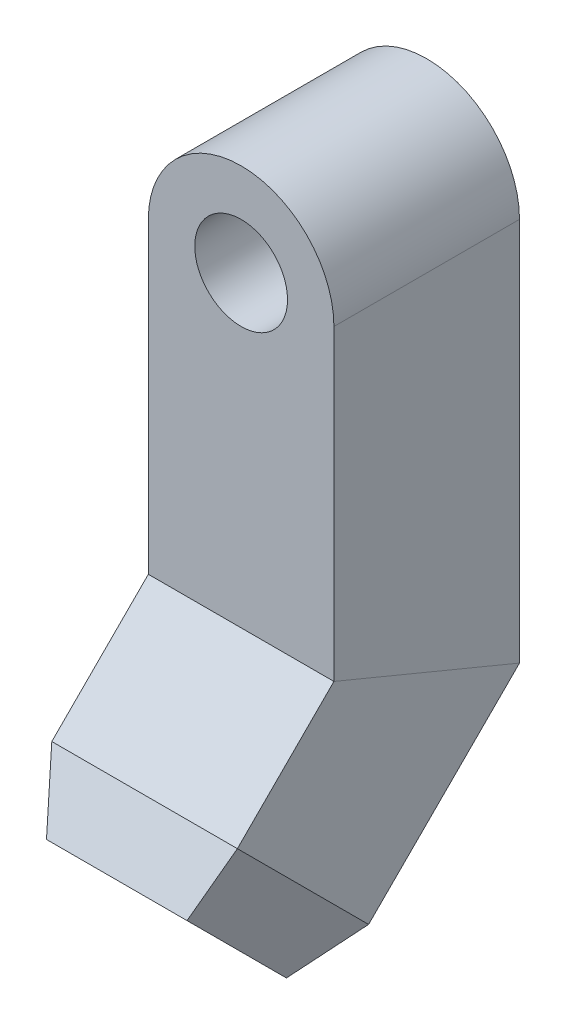
SolidWorks part; units mm, degrees
ref_plane "Front Plane" through (0, 0, 0) normal (0, 0, 1) x (1, 0, 0)
ref_plane "Top Plane" through (0, 0, 0) normal (0, 1, 0) x (1, 0, 0)
ref_plane "Right Plane" through (0, 0, 0) normal (1, 0, 0) x (0, 0, -1)
ref_plane "Plane2" through (0, 96.393, 0) normal (0, 1, 0) x (1, 0, 0)
sketch "Sketch10" plane through (0, 0, 0) normal (1, 0, 0) x (0, 0, -1)
  line L0 (0, 96.393) -> (0, 25.4)
  line L1 (55, 96.393) -> (-55, 96.393) construction
  line L2 (0, 25.4) -> (-25.4, 0)
  line L3 (55, 0) -> (-55, 0) construction
  dimension "D1" = 70.993
  dimension "D2" = 135
sketch "Sketch11" plane through (0, 96.393, 0) normal (0, 1, 0) x (1, 0, 0)
  line L1 (-19.05, -19.05) -> (19.05, -19.05)
  line L2 (-19.05, -19.05) -> (-19.05, 19.05)
  line L3 (-19.05, 19.05) -> (19.05, 19.05)
  line L4 (19.05, -19.05) -> (19.05, 19.05)
  line L5 (-19.05, -19.05) -> (19.05, 19.05) construction
  line L6 (-19.05, 19.05) -> (19.05, -19.05) construction
  point P0 (0, 0)
  dimension "D1" = 38.1
sweep "Sweep1" add profiles "Sketch11" path "Sketch10"
sketch "Sketch12" plane through (0, -12.7, 12.7) normal (0, -0.7071, 0.7071) x (1, 0, 0)
  line L8 (19.05, -1.0895) -> (19.05, 37.0105)
  line L9 (19.05, 37.0105) -> (-19.05, 37.0105)
  line L10 (-19.05, 37.0105) -> (-19.05, -1.0895)
  line L11 (-19.05, -1.0895) -> (19.05, -1.0895)
  line L12 (19.05, -1.0895) -> (19.05, 37.0105)
  line L13 (19.05, 37.0105) -> (-19.05, 37.0105)
  line L14 (-19.05, 37.0105) -> (-19.05, -1.0895)
  line L15 (-19.05, -1.0895) -> (19.05, -1.0895)
  dimension "D1" = 0
extrude "Boss-Extrude5" add sketch "Sketch12" along normal blind 12.7 draft 20
sketch "Sketch13" plane through (0, 0, -19.05) normal (0, 0, -1) x (-1, 0, 0)
  line L0 (55, 96.393) -> (-55, 96.393) construction
  line L1 (0, 55) -> (0, -55) construction
  line L2 (-19.05, 96.393) -> (19.05, 96.393)
  arc A0 (19.05, 96.393) -> (-19.05, 96.393) centre (0, 96.393) ccw
  dimension "D1" = 38.1
extrude "Boss-Extrude6" add sketch "Sketch13" against normal up to surface (38.1 mm away) up to face at (0, 64.8419, 19.05)
sketch "Sketch14" plane through (0, 0, 19.05) normal (0, 0, 1) x (1, 0, 0)
  circle A0 centre (0, 96.393) radius 9.525
  arc A1 (19.05, 96.393) -> (-19.05, 96.393) centre (0, 96.393) ccw construction
  dimension "D1" = 19.05
extrude "Cut-Extrude2" cut sketch "Sketch14" against normal blind 38.1
sketch "Sketch15" plane through (0, -21.6803, 21.6803) normal (0, -0.7071, 0.7071) x (1, 0, 0)
  line L0 (0, -34.9977) -> (0, 34.9977) construction
  line L4 (-14.4276, 32.3881) -> (-14.4276, 3.5329) construction
  line L5 (-14.4276, 3.5329) -> (14.4276, 3.5329) construction
  line L8 (0, 32.3881) -> (0, 3.5329) construction
  line L9 (14.4276, 32.3881) -> (-14.4276, 32.3881) construction
  circle A0 centre (0, 17.9605) radius 9.525
  point P12 (-14.4276, 17.9605)
  dimension "D1" = 19.05
extrude "Cut-Extrude3" cut sketch "Sketch15" against normal blind 12.7
